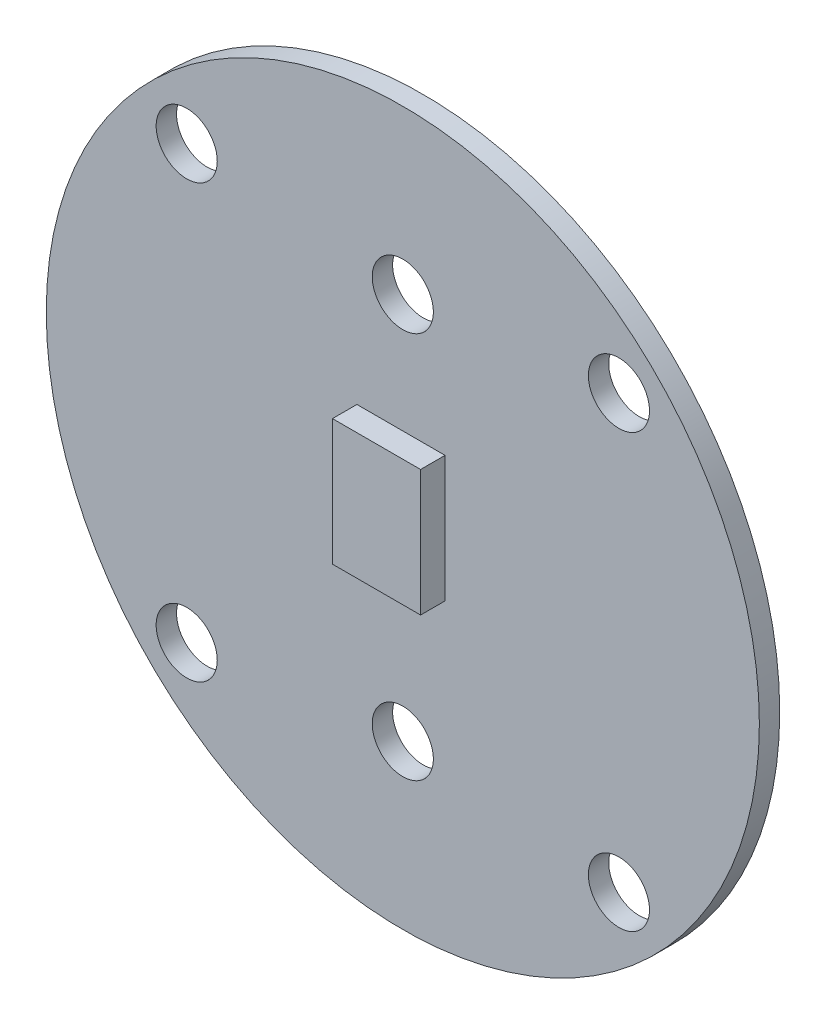
SolidWorks part; units mm, degrees
ref_plane "前视基准面" through (0, 0, 0) normal (0, 0, 1) x (1, 0, 0)
ref_plane "上视基准面" through (0, 0, 0) normal (0, 1, 0) x (1, 0, 0)
ref_plane "右视基准面" through (0, 0, 0) normal (1, 0, 0) x (0, 0, -1)
other "Configuration Table"
sketch "草图1" plane through (0, 0, 0) normal (0, 0, 1) x (1, 0, 0)
  line L0 (10.6066, 10.6066) -> (0, 0) construction
  line L1 (0, 0) -> (0, 2.9915) construction
  circle A0 centre (0, 0) radius 17.5
  circle A1 centre (0, 0) radius 9.5 construction
  circle A2 centre (0, 9.5) radius 1.5
  circle A3 centre (0, -9.5) radius 1.5
  circle A4 centre (0, 0) radius 15 construction
  circle A5 centre (10.6066, 10.6066) radius 1.5
  circle A6 centre (10.6066, -10.6066) radius 1.5
  circle A7 centre (-10.6066, -10.6066) radius 1.5
  circle A8 centre (-10.6066, 10.6066) radius 1.5
  point P11 (0, 0)
  point P13 (0, 0)
  point P21 (0, 0)
  dimension "D1" = 35
  dimension "D2" = 19
  dimension "D3" = 3
  dimension "D4" = 30
  dimension "D6" = 3
  dimension "D5" = 45
  dimension "D7" = 4
extrude "凸台-拉伸1" add sketch "草图1" along normal blind 1
sketch "草图2" plane through (0, 0, 1) normal (0, 0, 1) x (1, 0, 0)
  line L1 (-2.2527, 3.6944) -> (2.0725, 3.6944)
  line L2 (-2.2527, 3.6944) -> (-2.2527, -2.493)
  line L3 (-2.2527, -2.493) -> (2.0725, -2.493)
  line L4 (2.0725, 3.6944) -> (2.0725, -2.493)
extrude "凸台-拉伸2" add sketch "草图2" along normal blind 1.2
